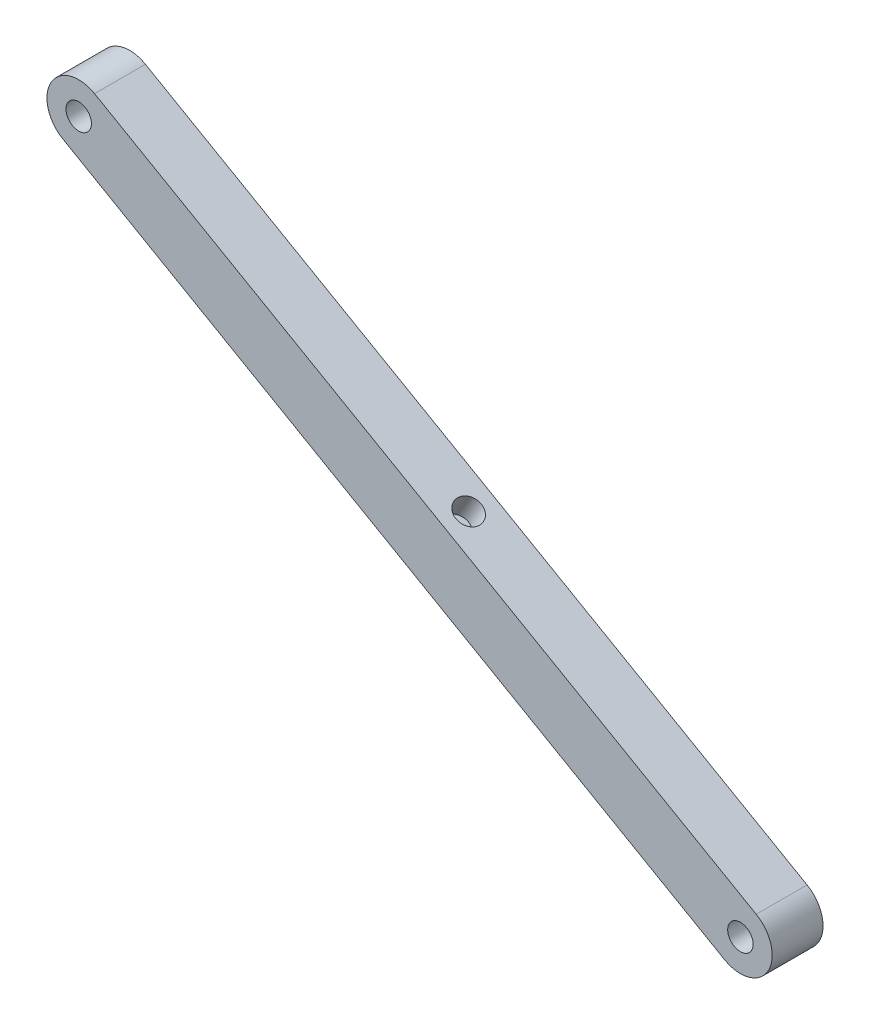
SolidWorks part; units mm, degrees
ref_plane "Спереди" through (0, 0, 0) normal (0, 0, 1) x (1, 0, 0)
ref_plane "Сверху" through (0, 0, 0) normal (0, 1, 0) x (1, 0, 0)
ref_plane "Справа" through (0, 0, 0) normal (1, 0, 0) x (0, 0, -1)
sketch "Sketch1" plane through (0, 0, 0) normal (0, 0, 1) x (1, 0, 0)
  line L0 (-5.265, 31.0446) -> (-57.3012, 60.9149) construction
  line L5 (-57.3012, 60.9149) -> (-5.265, 31.0446) construction
  line L6 (-56.0566, 63.083) -> (-4.0204, 33.2128)
  line L7 (-58.5458, 58.7467) -> (-6.5096, 28.8765)
  arc A2 (-56.0566, 63.083) -> (-58.5458, 58.7467) centre (-57.3012, 60.9149) ccw
  arc A3 (-6.5096, 28.8765) -> (-4.0204, 33.2128) centre (-5.265, 31.0446) ccw
  circle A4 centre (-57.3012, 60.9149) radius 1
  circle A5 centre (-5.265, 31.0446) radius 1
  point P2 (-31.2831, 45.9797)
  dimension "D3" = 2
  dimension "D1" = 60
  dimension "D2" = 5
extrude "Boss-Extrude1" add sketch "Sketch1" along normal blind 4
sketch "Sketch2" plane through (13.3435, 23.2454, 0) normal (0.4978, 0.8673, 0) x (0.8673, -0.4978, 0)
  line L0 (-50.3436, -2) -> (-46.6778, -2) construction
  line L2 (-48.4037, -4) -> (-48.4037, 0) construction
  circle A0 centre (-48.4037, -2) radius 1
  dimension "D1" = 2
extrude "Cut-Extrude1" cut sketch "Sketch2" against normal blind 2
